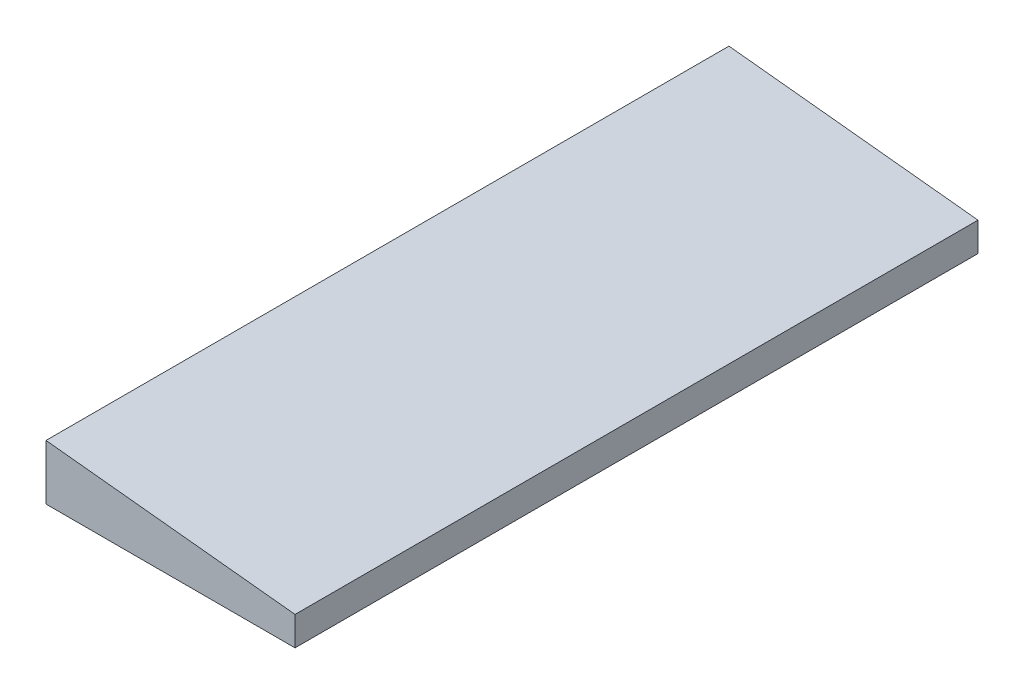
SolidWorks part; units mm, degrees
ref_plane "Front Plane" through (0, 0, 0) normal (0, 0, 1) x (1, 0, 0)
ref_plane "Top Plane" through (0, 0, 0) normal (0, 1, 0) x (1, 0, 0)
ref_plane "Right Plane" through (0, 0, 0) normal (1, 0, 0) x (0, 0, -1)
sketch "Sketch1" plane through (0, 0, 0) normal (0, 0, 1) x (1, 0, 0)
  line L0 (0, 0) -> (120.3371, 0)
  line L1 (120.3371, 0) -> (120.3371, 14)
  line L2 (120.3371, 14) -> (0, 26.6479)
  line L3 (0, 26.6479) -> (0, 0)
  line L4 (120.3371, 14) -> (0, 14) construction
  dimension "D1" = 6
  dimension "D2" = 121
  dimension "D3" = 14
extrude "Boss-Extrude1" add sketch "Sketch1" along normal mid plane 330
